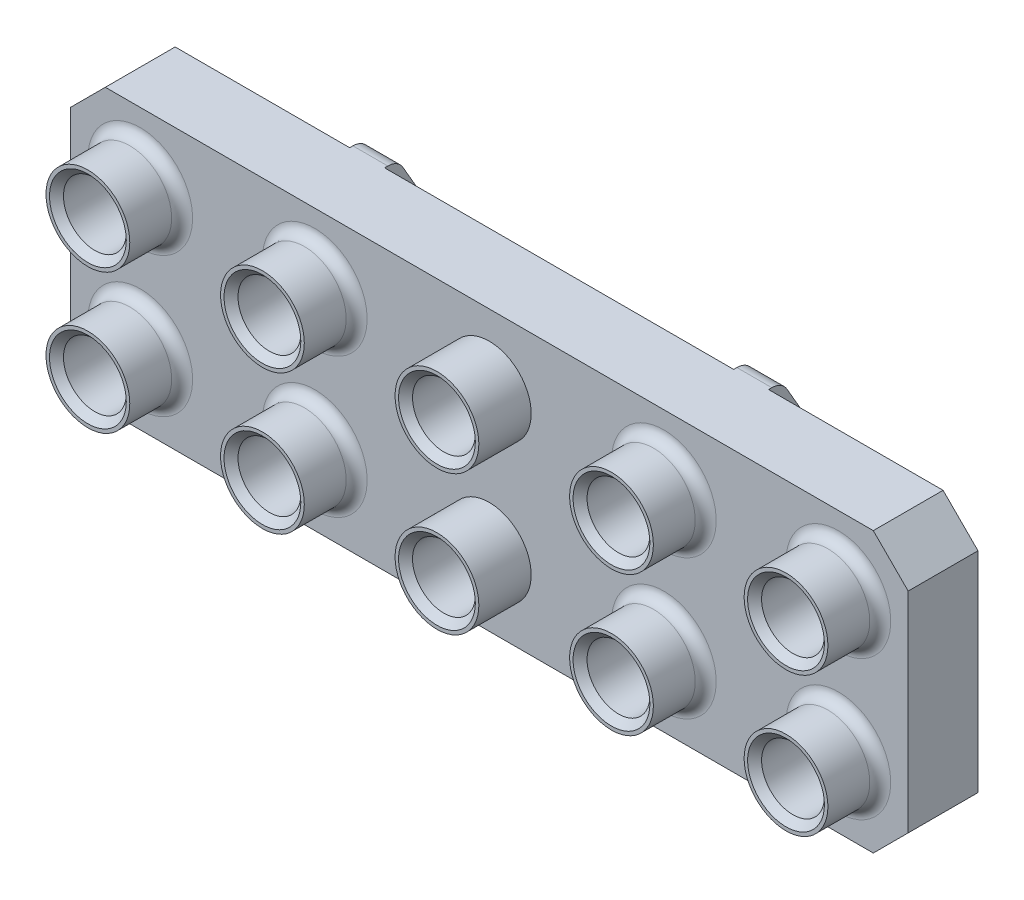
SolidWorks part; units mm, degrees
material "6061 合金"
ref_plane "前视基准面" through (0, 0, 0) normal (0, 0, 1) x (1, 0, 0)
ref_plane "上视基准面" through (0, 0, 0) normal (0, 1, 0) x (1, 0, 0)
ref_plane "右视基准面" through (0, 0, 0) normal (1, 0, 0) x (0, 0, -1)
sketch "草图1" plane through (0, 0, 0) normal (0, 0, 1) x (1, 0, 0)
  line L0 (-100, 40) -> (-100, 20) construction
  line L1 (-120, -40) -> (120, -40)
  line L2 (-120, -40) -> (-120, 40)
  line L3 (-120, 40) -> (120, 40)
  line L4 (120, -40) -> (120, 40)
  line L5 (-120, -40) -> (120, 40) construction
  line L6 (-120, 40) -> (120, -40) construction
  line L7 (-100, 20) -> (-120, 20) construction
  line L8 (-100, -20) -> (-100, 20) construction
  line L9 (-100, 20) -> (-50, 20) construction
  line L10 (-100, 0) -> (0, 0) construction
  line L11 (0, 20) -> (0, 0) construction
  circle A0 centre (-100, 20) radius 9 construction
  circle A1 centre (-50, 20) radius 9 construction
  circle A2 centre (0, 20) radius 9 construction
  circle A3 centre (50, 20) radius 9 construction
  circle A4 centre (100, 20) radius 9 construction
  circle A5 centre (-50, -20) radius 9 construction
  circle A6 centre (0, -20) radius 9 construction
  circle A7 centre (50, -20) radius 9 construction
  circle A8 centre (100, -20) radius 9 construction
  circle A17 centre (-100, -20) radius 9 construction
  point P0 (0, 0)
  dimension "D3" = 18
  dimension "D7" = 40
  dimension "D8" = 50
  dimension "D1" = 80
  dimension "D2" = 240
  dimension "D4" = 20
  dimension "D5" = 5
  dimension "D6" = 2
extrude "凸台-拉伸1" add sketch "草图1" along normal blind 20
sketch "草图2" plane through (0, 0, 20) normal (0, 0, 1) x (1, 0, 0)
  circle A0 centre (-100, 20) radius 9 construction
  circle A1 centre (-100, 20) radius 9
  circle A2 centre (-50, 20) radius 9
  circle A3 centre (0, 20) radius 9
  circle A4 centre (50, 20) radius 9
  circle A5 centre (100, 20) radius 9
  circle A6 centre (-50, -20) radius 9
  circle A7 centre (0, -20) radius 9
  circle A8 centre (50, -20) radius 9
  circle A9 centre (100, -20) radius 9
  circle A18 centre (-100, -20) radius 9
  circle A21 centre (-100, 20) radius 12
  circle A22 centre (-50, 20) radius 12
  circle A23 centre (0, 20) radius 12
  circle A24 centre (50, 20) radius 12
  circle A25 centre (100, 20) radius 12
  circle A26 centre (-50, -20) radius 12
  circle A27 centre (0, -20) radius 12
  circle A28 centre (50, -20) radius 12
  circle A29 centre (100, -20) radius 12
  circle A38 centre (-100, -20) radius 12
  dimension "D3" = 50
  dimension "D4" = 24
  dimension "D1" = 5
  dimension "D2" = 2
extrude "凸台-拉伸2" add sketch "草图2" along normal blind 15
sketch "草图3" plane through (0, 0, 20) normal (0, 0, 1) x (1, 0, 0)
  line L0 (-100, 20) -> (-50, 20) construction
  line L1 (-100, 20) -> (-100, -20) construction
  circle A0 centre (-100, 20) radius 9
  circle A1 centre (-50, 20) radius 9
  circle A2 centre (0, 20) radius 9
  circle A3 centre (50, 20) radius 9
  circle A4 centre (100, 20) radius 9
  circle A5 centre (-50, -20) radius 9
  circle A6 centre (0, -20) radius 9
  circle A7 centre (50, -20) radius 9
  circle A8 centre (100, -20) radius 9
  circle A17 centre (-100, -20) radius 9
  circle A20 centre (-100, 20) radius 9 construction
  circle A21 centre (-50, 20) radius 9 construction
  circle A22 centre (-100, -20) radius 9 construction
  point P4 (-61.8921, 21.0813)
  point P46 (0, 0)
  dimension "D2" = 5
  dimension "D3" = 2
extrude "切除-拉伸1" cut sketch "草图3" against normal blind 15
chamfer "倒角1" distance 10 angle 45 4 edges at (120, 40, 10) (120, -40, 10) (-120, -40, 10) (-120, 40, 10)
fillet "圆角1" radius 3 18 edges at (-112, 20, 20) (-91, -20, 5) (109, -20, 5) (59, -20, 5) (9, -20, 5) (-41, -20, 5) (109, 20, 5) (59, 20, 5) (9, 20, 5) (-41, 20, 5) (-91, 20, 5) (-62, 20, 20) (38, 20, 20) (88, 20, 20) (-62, -20, 20) (38, -20, 20) (88, -20, 20) (-112, -20, 20)
chamfer "倒角2" distance 2 angle 45 10 edges at (109, -20, 35) (59, -20, 35) (9, -20, 35) (-41, -20, 35) (-91, -20, 35) (109, 20, 35) (59, 20, 35) (9, 20, 35) (-41, 20, 35) (-91, 20, 35)
sketch "草图4" plane through (0, 0, 0) normal (1, 0, 0) x (0, 0, -1)
  line L0 (0, 40) -> (3.812, 40)
  line L1 (3.812, 40) -> (50, -40)
  line L2 (50, -40) -> (0, -40)
  line L3 (10, 9.282) -> (32.6795, -30)
  line L4 (32.6795, -30) -> (10, -30)
  line L5 (10, -30) -> (10, 9.282)
  line L6 (0, -30) -> (0, 30) construction
  line L7 (0, 40) -> (0, -40)
  dimension "D1" = 60
  dimension "D2" = 10
  dimension "D3" = 10
  dimension "D4" = 10
  dimension "D5" = 50
extrude "凸台-拉伸3" add sketch "草图4" along normal blind 10 from offset 50
mirror "镜向1" about plane through (0, 0, 0) normal (1, 0, 0) of "凸台-拉伸3"
fillet "圆角2" radius 5 9 edges at (-55, -30, -10) (-55, 9.282, -10) (55, 9.282, -10) (55, -30, -32.6795) (55, -30, -10) (-55, -40, -50) (-55, 40, -3.812) (55, -40, -50) (55, 40, -3.812)
